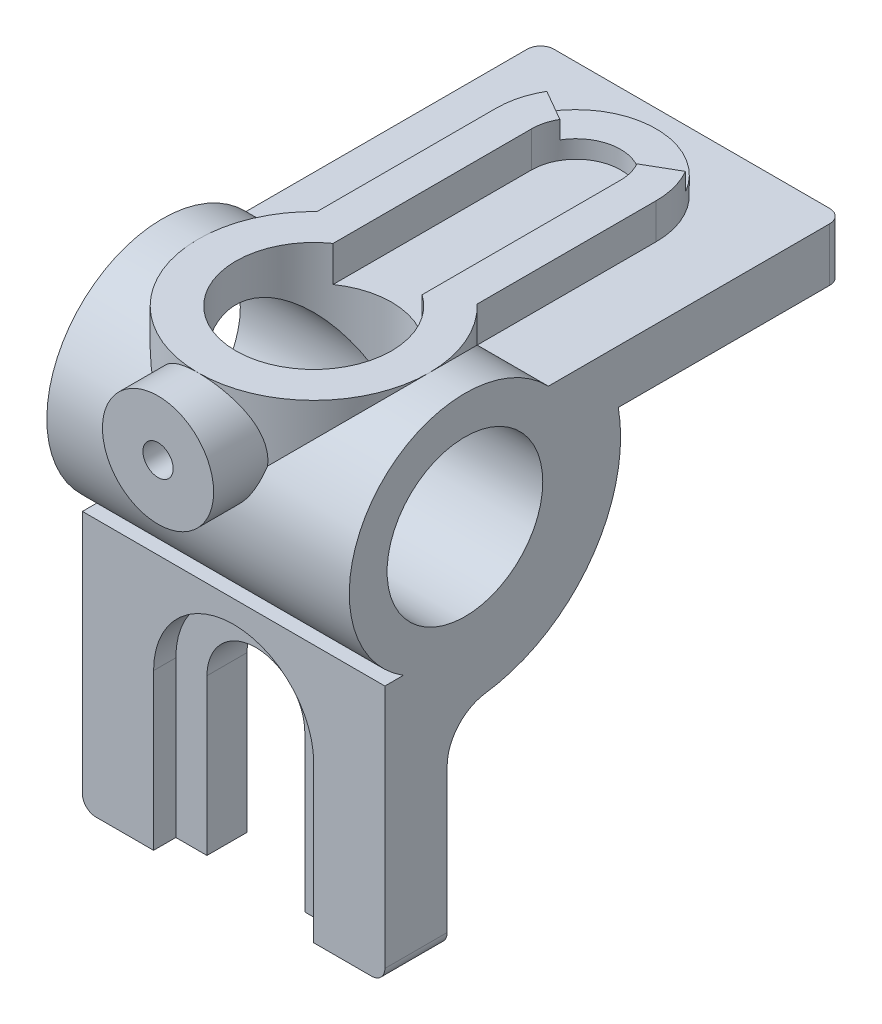
SolidWorks part; units mm, degrees
ref_plane "前视基准面" through (0, 0, 0) normal (0, 0, 1) x (1, 0, 0)
ref_plane "上视基准面" through (0, 0, 0) normal (0, 1, 0) x (1, 0, 0)
ref_plane "右视基准面" through (0, 0, 0) normal (1, 0, 0) x (0, 0, -1)
other "Configuration Table"
sketch "草图1" plane through (0, 0, 0) normal (1, 0, 0) x (0, 0, -1)
  line L1 (-18, -22) -> (-13.8564, -22)
  line L2 (-18, -22) -> (-18, -80)
  line L3 (-18, -80) -> (-4, -80)
  line L4 (-4, -25.6905) -> (-4, -80)
  arc A2 (-4, -25.6905) -> (-13.8564, -22) centre (0, 0) ccw
  dimension "D1" = 52
  dimension "D2" = 14
  dimension "D3" = 18
  dimension "D4" = 80
  dimension "D5" = 58
extrude "凸台-拉伸6" add sketch "草图1" along normal mid plane 68
ref_plane "基准面2" through (0, 0, 35) normal (0, 0, 1) x (1, 0, 0)
sketch "草图15" plane through (0, 0, 35) normal (0, 0, 1) x (1, 0, 0)
  circle A0 centre (0, 13.5) radius 12.5
  dimension "D1" = 25
  dimension "D2" = 13.5
extrude "凸台-拉伸7" add sketch "草图15" against normal up to surface (12.7795 mm away)
ref_plane "基准面4" through (0, 0, -85) normal (0, 0, 1) x (1, 0, 0)
sketch "草图16" plane through (0, 0, -85) normal (0, 0, 1) x (1, 0, 0)
  line L0 (-34, 26) -> (-34, -26) construction
  line L1 (-34, 18) -> (34, 18)
  line L2 (-34, 18) -> (-34, 6)
  line L3 (-34, 6) -> (34, 6)
  line L4 (34, 18) -> (34, 6)
  line L5 (34, -26) -> (34, 26) construction
  dimension "D1" = 12
  dimension "D2" = 6
extrude "凸台-拉伸8" add sketch "草图16" along normal up to surface (66.2383 mm away)
sketch "草图17" plane through (34, 0, 0) normal (1, 0, 0) x (0, 0, -1)
  line L0 (-4, -80) -> (-4, -25.6905) construction
  line L1 (25.2982, 6) -> (85, 6) construction
  line L2 (-4, -34.7707) -> (-4, -25.6905)
  line L3 (25.2982, 6) -> (34.4819, 6)
  arc A0 (-4, -25.6905) -> (25.2982, 6) centre (0, 0) ccw construction
  arc A1 (-4, -25.6905) -> (25.2982, 6) centre (0, 0) ccw
  arc A2 (-4, -34.7707) -> (34.4819, 6) centre (0, 0) ccw
  dimension "D1" = 70
extrude "凸台-拉伸9" add sketch "草图17" against normal blind 8
mirror "镜向2" about plane through (0, 0, 0) normal (1, 0, 0) of "凸台-拉伸9"
fillet "圆角2" radius 10 2 edges at (-30, -34.7707, 4) (30, -34.7707, 4)
ref_plane "基准面5" through (0, 26, 0) normal (0, 1, 0) x (1, 0, 0)
sketch "草图18" plane through (0, 26, 0) normal (0, 1, 0) x (1, 0, 0)
  line L0 (-18, 59) -> (-18, 18.7617)
  line L1 (18, 59) -> (18, 18.7617)
  arc A0 (-18, 18.7617) -> (18, 18.7617) centre (0, 0) ccw
  arc A1 (18, 59) -> (-18, 59) centre (0, 59) ccw
  dimension "D1" = 52
  dimension "D2" = 36
  dimension "D3" = 59
extrude "凸台-拉伸10" add sketch "草图18" against normal blind 19
sketch "草图19" plane through (0, 26, 0) normal (0, 1, 0) x (1, 0, 0)
  line L0 (-10, 59) -> (-10, 14.3614)
  line L1 (10, 59) -> (10, 14.3614)
  arc A0 (-10, 14.3614) -> (10, 14.3614) centre (0, 0) ccw
  arc A1 (10, 59) -> (-10, 59) centre (0, 59) ccw
  dimension "D1" = 20
  dimension "D2" = 35
  dimension "D3" = 59
extrude "切除-拉伸7" cut sketch "草图19" against normal blind 8
sketch "草图20" plane through (34, 0, 0) normal (1, 0, 0) x (0, 0, -1)
  circle A0 centre (0, 0) radius 17.5
  dimension "D1" = 35
extrude "切除-拉伸8" cut sketch "草图20" against normal up to surface (68 mm away) up to face at (-34, -22.1571, -15.4248)
sketch "草图21" plane through (0, 18, 0) normal (0, 1, 0) x (1, 0, 0)
  circle A0 centre (0, 0) radius 17.5
  dimension "D1" = 35
extrude "切除-拉伸9" cut sketch "草图21" against normal up to next
sketch "草图22" plane through (0, 0, 18) normal (0, 0, 1) x (1, 0, 0)
  line L0 (-18, -45) -> (-18, -80)
  line L1 (34, -80) -> (-34, -80) construction
  line L2 (-18, -80) -> (18, -80)
  line L3 (18, -80) -> (18, -45)
  arc A0 (18, -45) -> (-18, -45) centre (0, -45) ccw
  dimension "D1" = 36
  dimension "D2" = 45
  dimension "D3" = 36
extrude "切除-拉伸10" cut sketch "草图22" against normal blind 5
sketch "草图23" plane through (0, 0, 13) normal (0, 0, 1) x (1, 0, 0)
  line L0 (18, -80) -> (18, -45) construction
  line L1 (-18, -45) -> (-18, -80) construction
  line L2 (18, -80) -> (18, -45) construction
  line L3 (-18, -45) -> (-18, -80) construction
  line L4 (11, -80) -> (11, -45)
  line L5 (-11, -45) -> (-11, -80)
  line L6 (-11, -80) -> (11, -80)
  arc A0 (18, -45) -> (-18, -45) centre (0, -45) ccw construction
  arc A1 (18, -45) -> (-18, -45) centre (0, -45) ccw construction
  arc A2 (11, -45) -> (-11, -45) centre (0, -45) ccw
  dimension "D1" = 7
extrude "切除-拉伸11" cut sketch "草图23" against normal blind 9
sketch "草图24" plane through (0, 26, 0) normal (0, 1, 0) x (1, 0, 0)
  line L0 (0, 59) -> (0, 87.1289) construction
  line L1 (0, 59) -> (-15.5885, 68)
  line L2 (0, 59) -> (15.5885, 68)
  arc A0 (15.5885, 68) -> (-15.5885, 68) centre (0, 59) ccw
  arc A2 (18, 59) -> (-18, 59) centre (0, 59) ccw construction
  arc A3 (18, 59) -> (-18, 59) centre (0, 59) ccw construction
  dimension "D1" = 120
extrude "切除-拉伸12" cut sketch "草图24" against normal blind 4
fillet "圆角3" radius 3 4 edges at (34, -80, 11) (-34, -80, 11) (34, 12, -85) (-34, 12, -85)
hole_wizard "M8 螺纹孔1" positions "3D草图1" profile "草图25" tap size "M8" standard "ISO"
sketch3d "3D草图1"
  line L0 (0, 13.5, 22.8219) -> (0, 13.5, 35) construction
  point P0 (0, 13.5, 35)
sketch "草图25" plane through (0, 13.5, 35) normal (1, 0, 0) x (0, -1, 0)
  line L0 (0, 0) -> (0, 17.7929)
  line L1 (0, 17.7929) -> (3.4, 15.75)
  line L2 (3.4, 15.75) -> (3.4, 0)
  line L5 (3.4, 0) -> (0, 0)
  line L10 (0, 17.7929) -> (-3.4, 15.75) construction
  line L11 (0, -6.35) -> (0, 107.95) construction
  dimension "螺纹孔钻头直径" = 6.8
  dimension "螺纹孔钻头深度" = 15.75
  dimension "导头角度" = 118
cosmetic thread "孔螺纹线1" parameters "D1"=12, "D2"=8
